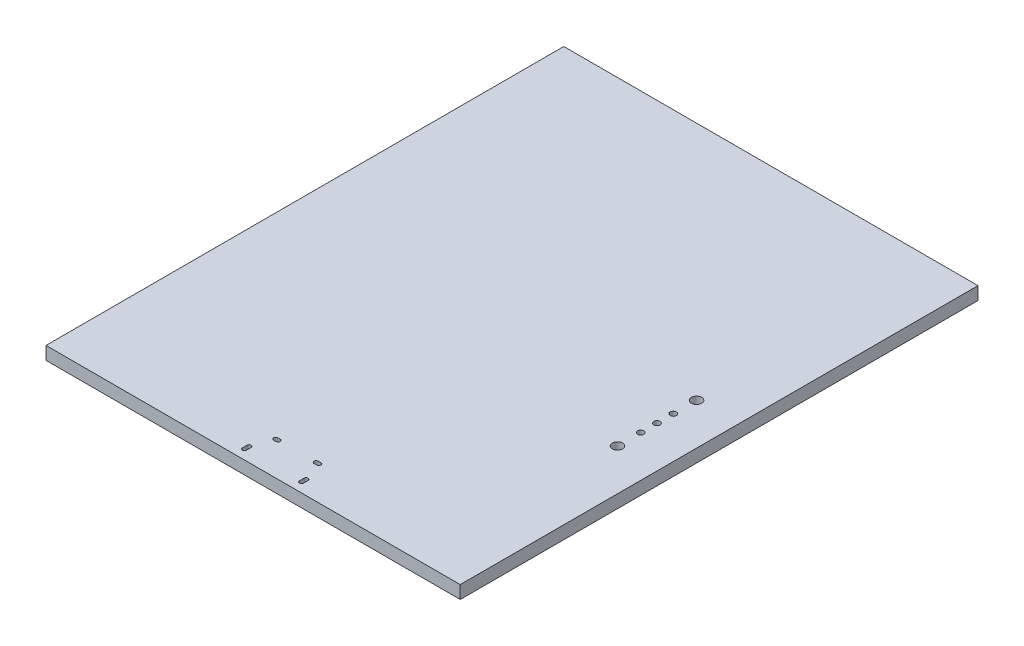
SolidWorks part; units mm, degrees
material "PCB Multi Layer"
ref_plane "Front Plane" through (0, 0, 0) normal (0, 0, 1) x (1, 0, 0)
ref_plane "Top Plane" through (0, 0, 0) normal (0, 1, 0) x (1, 0, 0)
ref_plane "Right Plane" through (0, 0, 0) normal (1, 0, 0) x (0, 0, -1)
sketch "Sketch1" plane through (0, 0, 0) normal (0, 1, 0) x (1, 0, 0)
  line L0 (-25.4, -31.75) -> (25.4, 31.75) construction
  line L1 (-25.4, 31.75) -> (25.4, 31.75)
  line L2 (-25.4, 31.75) -> (-25.4, -31.75)
  line L3 (-25.4, -31.75) -> (25.4, -31.75)
  line L4 (25.4, 31.75) -> (25.4, -31.75)
  dimension "D1" = 63.5
  dimension "D2" = 50.8
extrude "Boss-Extrude1" add sketch "Sketch1" along normal blind 1.5875
sketch "Sketch2" plane through (0, 1.5875, 0) normal (0, 1, 0) x (1, 0, 0)
  line L522 (-15.764, 14.9942) -> (-17.764, 14.9942)
  line L523 (-15.764, 15.9942) -> (-17.764, 15.9942)
  line L524 (-15.764, 15.9942) -> (-15.764, 14.9942)
  line L525 (-17.764, 15.9942) -> (-17.764, 14.9942)
  line L526 (-1.6002, 10.211) -> (-1.6002, 9.3474)
  line L527 (11.0676, -0.139) -> (11.5676, 0.361)
  line L528 (11.6969, -13.4784) -> (12.1969, -12.9784)
  line L529 (-15.764, 13.0892) -> (-17.764, 13.0892)
  line L530 (-15.764, 14.0892) -> (-17.764, 14.0892)
  line L531 (-15.764, 14.0892) -> (-15.764, 13.0892)
  line L532 (-17.764, 14.0892) -> (-17.764, 13.0892)
  line L533 (-8.51, 6.3982) -> (-10.54, 6.3982)
  line L534 (-8.51, 7.3182) -> (-10.54, 7.3182)
  line L535 (-8.51, 7.3182) -> (-8.51, 6.3982)
  line L536 (-10.54, 7.3182) -> (-10.54, 6.3982)
  line L537 (-9.779, 16.2562) -> (-9.779, 12.1922)
  line L538 (-8.001, 16.2562) -> (-8.001, 12.1922)
  line L539 (-9.779, 12.1922) -> (-8.001, 12.1922)
  line L540 (-9.779, 16.2562) -> (-8.001, 16.2562)
  line L541 (-9.263, 21.3522) -> (-9.263, 23.3522)
  line L542 (-8.263, 21.3522) -> (-8.263, 23.3522)
  line L543 (-8.263, 21.3522) -> (-9.263, 21.3522)
  line L544 (-8.263, 23.3522) -> (-9.263, 23.3522)
  line L545 (1.635, -15.1048) -> (-0.365, -15.1048)
  line L546 (1.635, -14.1048) -> (-0.365, -14.1048)
  line L547 (1.635, -14.1048) -> (1.635, -15.1048)
  line L548 (-0.365, -14.1048) -> (-0.365, -15.1048)
  line L549 (-0.46, -10.2858) -> (-0.46, -8.2558)
  line L550 (0.46, -10.2858) -> (0.46, -8.2558)
  line L551 (0.46, -10.2858) -> (-0.46, -10.2858)
  line L552 (0.46, -8.2558) -> (-0.46, -8.2558)
  line L553 (-0.365, -7.1198) -> (1.635, -7.1198)
  line L554 (-0.365, -8.1198) -> (1.635, -8.1198)
  line L555 (-0.365, -8.1198) -> (-0.365, -7.1198)
  line L556 (1.635, -8.1198) -> (1.635, -7.1198)
  line L557 (-0.373, 0.1432) -> (-0.373, 2.1432)
  line L561 (0.627, 0.1432) -> (0.627, 2.1432)
  line L562 (0.627, 0.1432) -> (-0.373, 0.1432)
  line L563 (0.627, 2.1432) -> (-0.373, 2.1432)
  line L564 (-1.643, 0.1432) -> (-1.643, 2.1432)
  line L565 (-0.643, 0.1432) -> (-0.643, 2.1432)
  line L566 (-0.643, 0.1432) -> (-1.643, 0.1432)
  line L567 (-0.643, 2.1432) -> (-1.643, 2.1432)
  line L571 (2.286, 21.1584) -> (-0.762, 21.1584)
  line L572 (-0.508, 21.1584) -> (-0.508, 20.2948)
  line L573 (0.1524, 20.2948) -> (0.1524, 21.1584)
  line L574 (-0.508, 20.2948) -> (0.1524, 20.2948)
  line L581 (1.3716, 21.1584) -> (1.3716, 20.2948)
  line L582 (1.3716, 20.2948) -> (2.032, 20.2948)
  line L583 (2.032, 20.2948) -> (2.032, 21.1584)
  line L584 (-0.762, 22.4284) -> (2.286, 22.4284)
  line L585 (1.0922, 23.292) -> (0.4318, 23.292)
  line L586 (0.4318, 23.292) -> (0.4318, 22.4284)
  line L587 (1.0922, 22.4284) -> (1.0922, 23.292)
  line L588 (2.286, 22.4284) -> (2.286, 21.1584)
  line L589 (-0.762, 21.1584) -> (-0.762, 22.4284)
  line L594 (6.555, -11.3248) -> (9.955, -11.3248)
  line L626 (6.555, -7.7248) -> (9.955, -7.7248)
  line L627 (9.955, -11.3248) -> (9.955, -7.7248)
  line L628 (6.555, -11.3248) -> (6.555, -7.7248)
  line L629 (8.001, 1.3972) -> (8.001, -2.6668)
  line L630 (9.779, 1.3972) -> (9.779, -2.6668)
  line L631 (8.001, -2.6668) -> (9.779, -2.6668)
  line L632 (8.001, 1.3972) -> (9.779, 1.3972)
  line L633 (7.24, 6.8102) -> (9.27, 6.8102)
  line L634 (7.24, 5.8902) -> (9.27, 5.8902)
  line L635 (7.24, 5.8902) -> (7.24, 6.8102)
  line L636 (9.27, 5.8902) -> (9.27, 6.8102)
  line L637 (15.74, -17.4148) -> (15.74, -19.4148)
  line L638 (14.74, -17.4148) -> (14.74, -19.4148)
  line L639 (14.74, -17.4148) -> (15.74, -17.4148)
  line L640 (14.74, -19.4148) -> (15.74, -19.4148)
  line L641 (14.351, 1.3972) -> (14.351, -2.6668)
  line L642 (16.129, 1.3972) -> (16.129, -2.6668)
  line L643 (14.351, -2.6668) -> (16.129, -2.6668)
  line L644 (14.351, 1.3972) -> (16.129, 1.3972)
  line L645 (15.105, 7.9852) -> (15.105, 5.9852)
  line L646 (14.105, 7.9852) -> (14.105, 5.9852)
  line L647 (14.105, 7.9852) -> (15.105, 7.9852)
  line L648 (14.105, 5.9852) -> (15.105, 5.9852)
  line L649 (13.835, 7.9852) -> (13.835, 5.9852)
  line L650 (12.835, 7.9852) -> (12.835, 5.9852)
  line L651 (12.835, 7.9852) -> (13.835, 7.9852)
  line L652 (12.835, 5.9852) -> (13.835, 5.9852)
  line L653 (-14.985, 10.1122) -> (-12.955, 10.1122)
  line L654 (-14.985, 9.1922) -> (-12.955, 9.1922)
  line L655 (-14.985, 9.1922) -> (-14.985, 10.1122)
  line L656 (-12.955, 9.1922) -> (-12.955, 10.1122)
  line L657 (-17.525, 10.1122) -> (-15.495, 10.1122)
  line L658 (-17.525, 9.1922) -> (-15.495, 9.1922)
  line L659 (-17.525, 9.1922) -> (-17.525, 10.1122)
  line L660 (-15.495, 9.1922) -> (-15.495, 10.1122)
  line L661 (-6.175, -19.4298) -> (-6.175, -17.3998)
  line L662 (-5.255, -19.4298) -> (-5.255, -17.3998)
  line L663 (-5.255, -19.4298) -> (-6.175, -19.4298)
  line L664 (-5.255, -17.3998) -> (-6.175, -17.3998)
  line L665 (-9.906, -18.4148) -> (-6.858, -18.4148)
  line L666 (-6.858, -20.1928) -> (-9.906, -20.1928)
  line L667 (-9.906, -20.1928) -> (-9.906, -18.4148)
  line L668 (-6.858, -18.4148) -> (-6.858, -20.1928)
  line L669 (-4.7, -4.6508) -> (-6.73, -4.6508)
  line L670 (-4.7, -3.7308) -> (-6.73, -3.7308)
  line L671 (-4.7, -3.7308) -> (-4.7, -4.6508)
  line L672 (-6.73, -3.7308) -> (-6.73, -4.6508)
  line L673 (-7.24, 17.9552) -> (-9.27, 17.9552)
  line L674 (-7.24, 18.8752) -> (-9.27, 18.8752)
  line L675 (-7.24, 18.8752) -> (-7.24, 17.9552)
  line L676 (-9.27, 18.8752) -> (-9.27, 17.9552)
  line L677 (-7.24, 16.6852) -> (-9.27, 16.6852)
  line L678 (-7.24, 17.6052) -> (-9.27, 17.6052)
  line L679 (-7.24, 17.6052) -> (-7.24, 16.6852)
  line L680 (-9.27, 17.6052) -> (-9.27, 16.6852)
  line L681 (-5.54, 3.4302) -> (-5.54, 5.4602)
  line L682 (-4.62, 3.4302) -> (-4.62, 5.4602)
  line L683 (-4.62, 3.4302) -> (-5.54, 3.4302)
  line L684 (-4.62, 5.4602) -> (-5.54, 5.4602)
  line L685 (-6.477, 9.2712) -> (-4.953, 9.2712)
  line L686 (-6.477, 13.5892) -> (-4.953, 13.5892)
  line L687 (-4.953, 13.5892) -> (-4.953, 9.2712)
  line L688 (-6.477, 13.5892) -> (-6.477, 9.2712)
  line L689 (-10.54, 8.5882) -> (-8.51, 8.5882)
  line L690 (-10.54, 7.6682) -> (-8.51, 7.6682)
  line L691 (-10.54, 7.6682) -> (-10.54, 8.5882)
  line L692 (-8.51, 7.6682) -> (-8.51, 8.5882)
  line L693 (-9.263, 23.8922) -> (-9.263, 25.8922)
  line L694 (-8.263, 23.8922) -> (-8.263, 25.8922)
  line L695 (-8.263, 23.8922) -> (-9.263, 23.8922)
  line L696 (-8.263, 25.8922) -> (-9.263, 25.8922)
  line L697 (1.659, -19.4148) -> (1.659, -17.4148)
  line L698 (2.659, -19.4148) -> (2.659, -17.4148)
  line L699 (2.659, -19.4148) -> (1.659, -19.4148)
  line L700 (2.659, -17.4148) -> (1.659, -17.4148)
  line L701 (0.635, -20.4468) -> (0.635, -16.3828)
  line L702 (-1.143, -20.4468) -> (-1.143, -16.3828)
  line L703 (0.635, -16.3828) -> (-1.143, -16.3828)
  line L704 (0.635, -20.4468) -> (-1.143, -20.4468)
  line L705 (-2.365, -19.4298) -> (-2.365, -17.3998)
  line L706 (-1.445, -19.4298) -> (-1.445, -17.3998)
  line L707 (-1.445, -19.4298) -> (-2.365, -19.4298)
  line L708 (-1.445, -17.3998) -> (-2.365, -17.3998)
  line L709 (1.635, -13.8348) -> (-0.365, -13.8348)
  line L710 (1.635, -12.8348) -> (-0.365, -12.8348)
  line L711 (1.635, -12.8348) -> (1.635, -13.8348)
  line L712 (-0.365, -12.8348) -> (-0.365, -13.8348)
  line L713 (1.65, -12.5248) -> (-0.38, -12.5248)
  line L714 (1.65, -11.6048) -> (-0.38, -11.6048)
  line L715 (1.65, -11.6048) -> (1.65, -12.5248)
  line L716 (-0.38, -11.6048) -> (-0.38, -12.5248)
  line L717 (-0.365, -5.8498) -> (1.635, -5.8498)
  line L718 (-0.365, -6.8498) -> (1.635, -6.8498)
  line L719 (-0.365, -6.8498) -> (-0.365, -5.8498)
  line L720 (1.635, -6.8498) -> (1.635, -5.8498)
  line L721 (-1.77, 23.7652) -> (-1.77, 25.7652)
  line L722 (-0.77, 23.7652) -> (-0.77, 25.7652)
  line L723 (-0.77, 23.7652) -> (-1.77, 23.7652)
  line L724 (-0.77, 25.7652) -> (-1.77, 25.7652)
  line L725 (2.04, 23.7652) -> (2.04, 25.7652)
  line L726 (3.04, 23.7652) -> (3.04, 25.7652)
  line L727 (3.04, 23.7652) -> (2.04, 23.7652)
  line L728 (3.04, 25.7652) -> (2.04, 25.7652)
  line L729 (0.254, 8.0774) -> (-2.794, 8.0774)
  line L730 (-2.54, 8.0774) -> (-2.54, 7.2138)
  line L731 (-1.8796, 7.2138) -> (-1.8796, 8.0774)
  line L732 (-2.54, 7.2138) -> (-1.8796, 7.2138)
  line L733 (-0.6604, 8.0774) -> (-0.6604, 7.2138)
  line L734 (-0.6604, 7.2138) -> (0, 7.2138)
  line L735 (0, 7.2138) -> (0, 8.0774)
  line L736 (-2.794, 9.3474) -> (0.254, 9.3474)
  line L737 (-0.9398, 10.211) -> (-1.6002, 10.211)
  line L738 (-0.9398, 9.3474) -> (-0.9398, 10.211)
  line L739 (0.254, 9.3474) -> (0.254, 8.0774)
  line L740 (-2.794, 8.0774) -> (-2.794, 9.3474)
  line L741 (11.049, -16.0018) -> (11.049, -11.9378)
  line L742 (9.271, -16.0018) -> (9.271, -11.9378)
  line L743 (11.049, -11.9378) -> (9.271, -11.9378)
  line L744 (11.049, -16.0018) -> (9.271, -16.0018)
  line L745 (10.287, -5.4608) -> (6.223, -5.4608)
  line L746 (10.287, -7.2388) -> (6.223, -7.2388)
  line L747 (6.223, -5.4608) -> (6.223, -7.2388)
  line L748 (10.287, -5.4608) -> (10.287, -7.2388)
  line L749 (8.644, -19.4148) -> (8.644, -17.4148)
  line L750 (9.644, -19.4148) -> (9.644, -17.4148)
  line L751 (9.644, -19.4148) -> (8.644, -19.4148)
  line L752 (9.644, -17.4148) -> (8.644, -17.4148)
  line L753 (7.374, -19.4148) -> (7.374, -17.4148)
  line L754 (8.374, -19.4148) -> (8.374, -17.4148)
  line L755 (8.374, -19.4148) -> (7.374, -19.4148)
  line L756 (8.374, -17.4148) -> (7.374, -17.4148)
  line L757 (5.588, -20.7008) -> (5.588, -17.3988)
  line L758 (7.112, -20.7008) -> (7.112, -17.3988)
  line L759 (7.112, -20.7008) -> (5.588, -20.7008)
  line L760 (7.112, -17.3988) -> (5.588, -17.3988)
  line L761 (5.255, 7.8752) -> (5.255, 9.9052)
  line L762 (6.175, 7.8752) -> (6.175, 9.9052)
  line L763 (6.175, 7.8752) -> (5.255, 7.8752)
  line L764 (6.175, 9.9052) -> (5.255, 9.9052)
  line L765 (6.553, 12.1792) -> (6.553, 7.3792)
  line L766 (9.653, 12.1792) -> (9.653, 7.3792)
  line L767 (9.653, 7.3792) -> (6.553, 7.3792)
  line L768 (9.653, 12.1792) -> (6.553, 12.1792)
  line L769 (5.85, 23.7652) -> (5.85, 25.7652)
  line L770 (6.85, 23.7652) -> (6.85, 25.7652)
  line L771 (6.85, 23.7652) -> (5.85, 23.7652)
  line L772 (6.85, 25.7652) -> (5.85, 25.7652)
  line L773 (9.555, 20.5152) -> (9.555, 16.3152)
  line L774 (6.955, 20.5152) -> (6.955, 16.3152)
  line L775 (6.955, 20.5152) -> (9.555, 20.5152)
  line L776 (6.955, 16.3152) -> (9.555, 16.3152)
  line L777 (11.168, 25.7652) -> (11.168, 23.7652)
  line L778 (10.168, 25.7652) -> (10.168, 23.7652)
  line L779 (10.168, 25.7652) -> (11.168, 25.7652)
  line L780 (10.168, 23.7652) -> (11.168, 23.7652)
  line L781 (9.858, 25.7802) -> (9.858, 23.7502)
  line L782 (8.938, 25.7802) -> (8.938, 23.7502)
  line L783 (8.938, 25.7802) -> (9.858, 25.7802)
  line L784 (8.938, 23.7502) -> (9.858, 23.7502)
  line L785 (8.588, 25.7802) -> (8.588, 23.7502)
  line L786 (7.668, 25.7802) -> (7.668, 23.7502)
  line L787 (7.668, 25.7802) -> (8.588, 25.7802)
  line L788 (7.668, 23.7502) -> (8.588, 23.7502)
  line L789 (14.43, -4.6998) -> (14.43, -6.7298)
  line L790 (13.51, -4.6998) -> (13.51, -6.7298)
  line L791 (13.51, -4.6998) -> (14.43, -4.6998)
  line L792 (13.51, -6.7298) -> (14.43, -6.7298)
  line L793 (12.573, -19.6848) -> (12.573, -16.3828)
  line L794 (14.097, -19.6848) -> (14.097, -16.3828)
  line L795 (14.097, -19.6848) -> (12.573, -19.6848)
  line L796 (14.097, -16.3828) -> (12.573, -16.3828)
  line L797 (14.351, -11.8108) -> (14.351, -15.8748)
  line L798 (16.129, -11.8108) -> (16.129, -15.8748)
  line L799 (14.351, -15.8748) -> (16.129, -15.8748)
  line L800 (14.351, -11.8108) -> (16.129, -11.8108)
  line L801 (13.51, 23.7502) -> (13.51, 25.7802)
  line L802 (14.43, 23.7502) -> (14.43, 25.7802)
  line L803 (14.43, 23.7502) -> (13.51, 23.7502)
  line L804 (14.43, 25.7802) -> (13.51, 25.7802)
  line L805 (15.74, 25.7652) -> (15.74, 23.7652)
  line L806 (14.74, 25.7652) -> (14.74, 23.7652)
  line L807 (14.74, 25.7652) -> (15.74, 25.7652)
  line L808 (14.74, 23.7652) -> (15.74, 23.7652)
  line L809 (16.05, 23.7502) -> (16.05, 25.7802)
  line L810 (16.97, 23.7502) -> (16.97, 25.7802)
  line L811 (16.97, 23.7502) -> (16.05, 23.7502)
  line L812 (16.97, 25.7802) -> (16.05, 25.7802)
  line L813 (17.32, 23.7502) -> (17.32, 25.7802)
  line L814 (18.24, 23.7502) -> (18.24, 25.7802)
  line L815 (18.24, 23.7502) -> (17.32, 23.7502)
  line L816 (18.24, 25.7802) -> (17.32, 25.7802)
  line L817 (13.089, 16.7802) -> (13.089, 18.7802)
  line L818 (14.089, 16.7802) -> (14.089, 18.7802)
  line L819 (14.089, 16.7802) -> (13.089, 16.7802)
  line L820 (14.089, 18.7802) -> (13.089, 18.7802)
  line L821 (16.05, 16.7652) -> (16.05, 18.7952)
  line L822 (16.97, 16.7652) -> (16.97, 18.7952)
  line L823 (16.97, 16.7652) -> (16.05, 16.7652)
  line L824 (16.97, 18.7952) -> (16.05, 18.7952)
  line L825 (15.74, 18.7802) -> (15.74, 16.7802)
  line L826 (14.74, 18.7802) -> (14.74, 16.7802)
  line L827 (14.74, 18.7802) -> (15.74, 18.7802)
  line L828 (14.74, 16.7802) -> (15.74, 16.7802)
  line L829 (-0.373, -2.3968) -> (-0.373, -0.3968)
  line L830 (0.627, -2.3968) -> (0.627, -0.3968)
  line L831 (0.627, -2.3968) -> (-0.373, -2.3968)
  line L832 (0.627, -0.3968) -> (-0.373, -0.3968)
  line L833 (-0.643, -0.3968) -> (-0.643, -2.3968)
  line L834 (-1.643, -0.3968) -> (-1.643, -2.3968)
  line L835 (-1.643, -0.3968) -> (-0.643, -0.3968)
  line L836 (-1.643, -2.3968) -> (-0.643, -2.3968)
  line L837 (10.168, 21.2252) -> (10.168, 23.2252)
  line L838 (11.168, 21.2252) -> (11.168, 23.2252)
  line L839 (11.168, 21.2252) -> (10.168, 21.2252)
  line L840 (11.168, 23.2252) -> (10.168, 23.2252)
  line L841 (-17.478, -18.7948) -> (-17.478, -16.7648)
  line L842 (-16.558, -18.7948) -> (-16.558, -16.7648)
  line L843 (-16.558, -18.7948) -> (-17.478, -18.7948)
  line L844 (-16.558, -16.7648) -> (-17.478, -16.7648)
  line L845 (-15.926, -15.3798) -> (-15.926, -20.1798)
  line L846 (-12.826, -15.3798) -> (-12.826, -20.1798)
  line L847 (-12.826, -20.1798) -> (-15.926, -20.1798)
  line L848 (-12.826, -15.3798) -> (-15.926, -15.3798)
  line L849 (-9.145, -17.0968) -> (-11.175, -17.0968)
  line L850 (-9.145, -16.1768) -> (-11.175, -16.1768)
  line L851 (-9.145, -16.1768) -> (-9.145, -17.0968)
  line L852 (-11.175, -16.1768) -> (-11.175, -17.0968)
  line L853 (-12.573, -8.6358) -> (-16.637, -8.6358)
  line L854 (-12.573, -10.4138) -> (-16.637, -10.4138)
  line L855 (-16.637, -8.6358) -> (-16.637, -10.4138)
  line L856 (-12.573, -8.6358) -> (-12.573, -10.4138)
  line L857 (-15.62, -7.1598) -> (-13.59, -7.1598)
  line L858 (-15.62, -8.0798) -> (-13.59, -8.0798)
  line L859 (-15.62, -8.0798) -> (-15.62, -7.1598)
  line L860 (-13.59, -8.0798) -> (-13.59, -7.1598)
  line L861 (-17.137, -4.1748) -> (-17.137, -2.1748)
  line L862 (-16.137, -4.1748) -> (-16.137, -2.1748)
  line L863 (-16.137, -4.1748) -> (-17.137, -4.1748)
  line L864 (-16.137, -2.1748) -> (-17.137, -2.1748)
  line L865 (-16.137, 0.3652) -> (-16.137, -1.6348)
  line L866 (-17.137, 0.3652) -> (-17.137, -1.6348)
  line L867 (-17.137, 0.3652) -> (-16.137, 0.3652)
  line L868 (-17.137, -1.6348) -> (-16.137, -1.6348)
  line L869 (-10.16, 12.1922) -> (-10.16, 16.2562)
  line L870 (-11.938, 12.1922) -> (-11.938, 16.2562)
  line L871 (-10.16, 16.2562) -> (-11.938, 16.2562)
  line L872 (-10.16, 12.1922) -> (-11.938, 12.1922)
  line L873 (7.747, -20.9548) -> (3.683, -20.9548)
  line L874 (7.747, -22.7328) -> (3.683, -22.7328)
  line L875 (3.683, -20.9548) -> (3.683, -22.7328)
  line L876 (7.747, -20.9548) -> (7.747, -22.7328)
  line L877 (2.929, -17.0018) -> (2.929, -15.0018)
  line L878 (3.929, -17.0018) -> (3.929, -15.0018)
  line L879 (3.929, -17.0018) -> (2.929, -17.0018)
  line L880 (3.929, -15.0018) -> (2.929, -15.0018)
  line L881 (1.65, -16.3348) -> (-0.38, -16.3348)
  line L882 (1.65, -15.4148) -> (-0.38, -15.4148)
  line L883 (1.65, -15.4148) -> (1.65, -16.3348)
  line L884 (-0.38, -15.4148) -> (-0.38, -16.3348)
  line L885 (4.445, -12.0648) -> (4.445, -8.0008)
  line L886 (2.667, -12.0648) -> (2.667, -8.0008)
  line L887 (4.445, -8.0008) -> (2.667, -8.0008)
  line L888 (4.445, -12.0648) -> (2.667, -12.0648)
  line L889 (10.7, -8.4248) -> (11.2, -7.9248)
  line L890 (10.7, -7.9248) -> (10.7, -11.1248)
  line L891 (14.7, -7.9248) -> (14.7, -11.1248)
  line L892 (10.7, -11.1248) -> (14.7, -11.1248)
  line L893 (10.7, -7.9248) -> (14.7, -7.9248)
  line L894 (2.167, 0.1432) -> (2.167, 2.1432)
  line L895 (3.167, 0.1432) -> (3.167, 2.1432)
  line L896 (3.167, 0.1432) -> (2.167, 0.1432)
  line L897 (3.167, 2.1432) -> (2.167, 2.1432)
  line L898 (0.897, 0.1432) -> (0.897, 2.1432)
  line L899 (1.897, 0.1432) -> (1.897, 2.1432)
  line L900 (1.897, 0.1432) -> (0.897, 0.1432)
  line L901 (1.897, 2.1432) -> (0.897, 2.1432)
  line L902 (11.065, 0.3652) -> (11.065, -1.6348)
  line L903 (13.065, 0.3652) -> (13.065, -1.6348)
  line L904 (11.065, -1.6348) -> (13.065, -1.6348)
  line L905 (11.065, 0.3652) -> (13.065, 0.3652)
  line L906 (-2.913, 0.1432) -> (-2.913, 2.1432)
  line L907 (-1.913, 0.1432) -> (-1.913, 2.1432)
  line L908 (-1.913, 0.1432) -> (-2.913, 0.1432)
  line L909 (-1.913, 2.1432) -> (-2.913, 2.1432)
  line L910 (3.477, 0.1282) -> (3.477, 2.1582)
  line L911 (4.397, 0.1282) -> (4.397, 2.1582)
  line L912 (4.397, 0.1282) -> (3.477, 0.1282)
  line L913 (4.397, 2.1582) -> (3.477, 2.1582)
  line L914 (12.445, 7.6682) -> (10.415, 7.6682)
  line L915 (12.445, 8.5882) -> (10.415, 8.5882)
  line L916 (12.445, 8.5882) -> (12.445, 7.6682)
  line L917 (10.415, 8.5882) -> (10.415, 7.6682)
  line L918 (-5.445, 8.1202) -> (-3.445, 8.1202)
  line L919 (-5.445, 7.1202) -> (-3.445, 7.1202)
  line L920 (-5.445, 7.1202) -> (-5.445, 8.1202)
  line L921 (-3.445, 7.1202) -> (-3.445, 8.1202)
  line L922 (12.445, 6.5252) -> (10.415, 6.5252)
  line L923 (12.445, 7.4452) -> (10.415, 7.4452)
  line L924 (12.445, 7.4452) -> (12.445, 6.5252)
  line L925 (10.415, 7.4452) -> (10.415, 6.5252)
  line L926 (4.362, 6.0182) -> (4.762, 6.0182)
  line L927 (-2.838, 6.0182) -> (-3.238, 6.0182)
  line L928 (-2.838, 3.4182) -> (4.362, 3.4182)
  line L929 (-3.202, 3.1182) -> (4.762, 3.1182)
  line L930 (-3.238, 6.4182) -> (4.762, 6.4182)
  line L931 (4.762, 3.1182) -> (4.762, 6.4182)
  line L932 (4.362, 6.0182) -> (4.362, 3.4182)
  line L933 (-3.238, 3.1182) -> (-3.238, 6.4182)
  line L934 (-2.838, 3.4182) -> (-2.838, 6.0182)
  line L935 (-1.23, 3.8102) -> (-1.23, 4.8262)
  line L936 (-1.23, 4.8262) -> (-2.246, 4.8262)
  line L937 (-2.246, 4.8262) -> (-2.246, 3.8102)
  line L938 (-2.246, 3.8102) -> (-1.23, 3.8102)
  line L939 (4.318, 15.4942) -> (4.318, 11.4302)
  line L940 (6.096, 15.4942) -> (6.096, 11.4302)
  line L941 (4.318, 11.4302) -> (6.096, 11.4302)
  line L942 (4.318, 15.4942) -> (6.096, 15.4942)
  line L943 (18.24, 15.6202) -> (18.24, 13.5902)
  line L944 (17.32, 15.6202) -> (17.32, 13.5902)
  line L945 (17.32, 15.6202) -> (18.24, 15.6202)
  line L946 (17.32, 13.5902) -> (18.24, 13.5902)
  line L947 (-1.524, 21.1584) -> (-4.572, 21.1584)
  line L948 (-4.318, 21.1584) -> (-4.318, 20.2948)
  line L949 (-3.6576, 20.2948) -> (-3.6576, 21.1584)
  line L950 (-4.318, 20.2948) -> (-3.6576, 20.2948)
  line L951 (-2.4384, 21.1584) -> (-2.4384, 20.2948)
  line L952 (-2.4384, 20.2948) -> (-1.778, 20.2948)
  line L953 (-1.778, 20.2948) -> (-1.778, 21.1584)
  line L954 (-4.572, 22.4284) -> (-1.524, 22.4284)
  line L955 (-2.7178, 23.292) -> (-3.3782, 23.292)
  line L956 (-3.3782, 23.292) -> (-3.3782, 22.4284)
  line L957 (-2.7178, 22.4284) -> (-2.7178, 23.292)
  line L958 (-1.524, 22.4284) -> (-1.524, 21.1584)
  line L959 (-4.572, 21.1584) -> (-4.572, 22.4284)
  line L960 (6.096, 21.1584) -> (3.048, 21.1584)
  line L961 (3.302, 21.1584) -> (3.302, 20.2948)
  line L962 (3.9624, 20.2948) -> (3.9624, 21.1584)
  line L963 (3.302, 20.2948) -> (3.9624, 20.2948)
  line L964 (5.1816, 21.1584) -> (5.1816, 20.2948)
  line L965 (5.1816, 20.2948) -> (5.842, 20.2948)
  line L966 (5.842, 20.2948) -> (5.842, 21.1584)
  line L967 (3.048, 22.4284) -> (6.096, 22.4284)
  line L968 (4.9022, 23.292) -> (4.2418, 23.292)
  line L969 (4.2418, 23.292) -> (4.2418, 22.4284)
  line L970 (4.9022, 22.4284) -> (4.9022, 23.292)
  line L971 (6.096, 22.4284) -> (6.096, 21.1584)
  line L972 (3.048, 21.1584) -> (3.048, 22.4284)
  line L973 (18.24, 23.2402) -> (18.24, 21.2102)
  line L974 (17.32, 23.2402) -> (17.32, 21.2102)
  line L975 (17.32, 23.2402) -> (18.24, 23.2402)
  line L976 (17.32, 21.2102) -> (18.24, 21.2102)
  line L977 (13.51, 21.2102) -> (13.51, 23.2402)
  line L978 (14.43, 21.2102) -> (14.43, 23.2402)
  line L979 (14.43, 21.2102) -> (13.51, 21.2102)
  line L980 (14.43, 23.2402) -> (13.51, 23.2402)
  line L981 (16.97, 23.2402) -> (16.97, 21.2102)
  line L982 (16.05, 23.2402) -> (16.05, 21.2102)
  line L983 (16.05, 23.2402) -> (16.97, 23.2402)
  line L984 (16.05, 21.2102) -> (16.97, 21.2102)
  line L985 (15.74, 23.2252) -> (15.74, 21.2252)
  line L986 (14.74, 23.2252) -> (14.74, 21.2252)
  line L987 (14.74, 23.2252) -> (15.74, 23.2252)
  line L988 (14.74, 21.2252) -> (15.74, 21.2252)
  line L989 (-12.573, -11.1758) -> (-16.637, -11.1758)
  line L990 (-12.573, -12.9538) -> (-16.637, -12.9538)
  line L991 (-16.637, -11.1758) -> (-16.637, -12.9538)
  line L992 (-12.573, -11.1758) -> (-12.573, -12.9538)
  line L993 (-15.62, -20.4948) -> (-13.59, -20.4948)
  line L994 (-15.62, -21.4148) -> (-13.59, -21.4148)
  line L995 (-15.62, -21.4148) -> (-15.62, -20.4948)
  line L996 (-13.59, -21.4148) -> (-13.59, -20.4948)
  line L997 (-19.105, 17.4752) -> (-19.105, 26.9752)
  line L998 (-10.105, 17.4752) -> (-10.105, 26.9752)
  line L999 (-19.105, 17.4752) -> (-10.105, 17.4752)
  line L1000 (-19.105, 26.9752) -> (-10.105, 26.9752)
  line L1001 (-12.02, 8.2652) -> (-11.42, 7.6652)
  line L1002 (-11.42, 8.2652) -> (-16.52, 8.2652)
  line L1003 (-11.42, 3.1652) -> (-16.52, 3.1652)
  line L1004 (-16.52, 8.2652) -> (-16.52, 3.1652)
  line L1005 (-11.42, 8.2652) -> (-11.42, 3.1652)
  line L1006 (11.7, -12.9698) -> (11.7, -14.9698)
  line L1007 (13.7, -12.9698) -> (13.7, -14.9698)
  line L1008 (11.7, -14.9698) -> (13.7, -14.9698)
  line L1009 (11.7, -12.9698) -> (13.7, -12.9698)
  line L1010 (-3.945, -17.4148) -> (-3.945, -19.4148)
  line L1011 (-4.945, -17.4148) -> (-4.945, -19.4148)
  line L1012 (-4.945, -17.4148) -> (-3.945, -17.4148)
  line L1013 (-4.945, -19.4148) -> (-3.945, -19.4148)
  line L1014 (-2.675, -17.4148) -> (-2.675, -19.4148)
  line L1015 (-3.675, -17.4148) -> (-3.675, -19.4148)
  line L1016 (-3.675, -17.4148) -> (-2.675, -17.4148)
  line L1017 (-3.675, -19.4148) -> (-2.675, -19.4148)
  line L1018 (11.184, -19.4148) -> (11.184, -17.4148)
  line L1019 (12.184, -19.4148) -> (12.184, -17.4148)
  line L1020 (12.184, -19.4148) -> (11.184, -19.4148)
  line L1021 (12.184, -17.4148) -> (11.184, -17.4148)
  line L1022 (4.961, -9.7628) -> (4.961, -7.7628)
  line L1023 (5.961, -9.7628) -> (5.961, -7.7628)
  line L1024 (5.961, -9.7628) -> (4.961, -9.7628)
  line L1025 (5.961, -7.7628) -> (4.961, -7.7628)
  line L1026 (8.45, -16.1048) -> (7.85, -16.7048)
  line L1027 (8.45, -16.7048) -> (8.45, -12.5048)
  line L1028 (4.25, -16.7048) -> (4.25, -12.5048)
  line L1029 (8.45, -12.5048) -> (4.25, -12.5048)
  line L1030 (8.45, -16.7048) -> (4.25, -16.7048)
  line L1031 (3.056, -19.4148) -> (3.056, -17.4148)
  line L1032 (4.056, -19.4148) -> (4.056, -17.4148)
  line L1033 (4.056, -19.4148) -> (3.056, -19.4148)
  line L1034 (4.056, -17.4148) -> (3.056, -17.4148)
  line L1035 (9.914, -19.4148) -> (9.914, -17.4148)
  line L1036 (10.914, -19.4148) -> (10.914, -17.4148)
  line L1037 (10.914, -19.4148) -> (9.914, -19.4148)
  line L1038 (10.914, -17.4148) -> (9.914, -17.4148)
  line L1039 (13.7, -12.5648) -> (11.7, -12.5648)
  line L1040 (13.7, -11.5648) -> (11.7, -11.5648)
  line L1041 (13.7, -11.5648) -> (13.7, -12.5648)
  line L1042 (11.7, -11.5648) -> (11.7, -12.5648)
  line L1043 (11.89, -4.6998) -> (11.89, -6.7298)
  line L1044 (10.97, -4.6998) -> (10.97, -6.7298)
  line L1045 (10.97, -4.6998) -> (11.89, -4.6998)
  line L1046 (10.97, -6.7298) -> (11.89, -6.7298)
  line L1047 (16.389, 9.8652) -> (15.789, 9.2652)
  line L1048 (16.389, 9.2652) -> (16.389, 14.8652)
  line L1049 (10.789, 9.2652) -> (10.789, 14.8652)
  line L1050 (16.389, 14.8652) -> (10.789, 14.8652)
  line L1051 (16.389, 9.2652) -> (10.789, 9.2652)
  line L1052 (1.016, 10.6682) -> (-3.556, 10.6682)
  line L1053 (-3.556, 13.4622) -> (1.016, 13.4622)
  line L1054 (1.016, 10.6682) -> (1.016, 13.4622)
  line L1055 (-3.556, 10.6682) -> (-3.556, 13.4622)
  line L1056 (17.645, 4.1752) -> (17.645, 2.1752)
  line L1057 (16.645, 4.1752) -> (16.645, 2.1752)
  line L1058 (16.645, 4.1752) -> (17.645, 4.1752)
  line L1059 (16.645, 2.1752) -> (17.645, 2.1752)
  line L1060 (6.096, 15.6212) -> (6.096, 19.6852)
  line L1061 (4.318, 15.6212) -> (4.318, 19.6852)
  line L1062 (6.096, 19.6852) -> (4.318, 19.6852)
  line L1063 (6.096, 15.6212) -> (4.318, 15.6212)
  line L1064 (17.399, 10.0332) -> (17.399, 13.3352)
  line L1065 (18.923, 10.0332) -> (18.923, 13.3352)
  line L1066 (18.923, 10.0332) -> (17.399, 10.0332)
  line L1067 (18.923, 13.3352) -> (17.399, 13.3352)
  line L1068 (3.762, 18.1602) -> (3.762, 16.1302)
  line L1069 (2.842, 18.1602) -> (2.842, 16.1302)
  line L1070 (2.842, 18.1602) -> (3.762, 18.1602)
  line L1071 (2.842, 16.1302) -> (3.762, 16.1302)
  line L1072 (-4.953, 18.6692) -> (-6.477, 18.6692)
  line L1073 (-4.953, 14.3512) -> (-6.477, 14.3512)
  line L1074 (-6.477, 14.3512) -> (-6.477, 18.6692)
  line L1075 (-4.953, 14.3512) -> (-4.953, 18.6692)
  line L1076 (-2.97, 15.7102) -> (-2.97, 14.5102)
  line L1077 (-3.57, 15.1102) -> (-2.37, 15.1102)
  line L1078 (1.43, 17.8102) -> (0.33, 18.9102)
  line L1079 (-3.97, 18.9102) -> (-3.97, 14.1102)
  line L1080 (1.43, 17.8102) -> (1.43, 14.1102)
  line L1081 (-3.97, 14.1102) -> (1.43, 14.1102)
  line L1082 (-3.97, 18.9102) -> (0.33, 18.9102)
  line L1083 (2.922, 11.0012) -> (4.952, 11.0012)
  line L1084 (2.922, 10.0812) -> (4.952, 10.0812)
  line L1085 (2.922, 10.0812) -> (2.922, 11.0012)
  line L1086 (4.952, 10.0812) -> (4.952, 11.0012)
  line L1087 (4.318, 11.4302) -> (4.318, 15.4942)
  line L1088 (2.54, 11.4302) -> (2.54, 15.4942)
  line L1089 (4.318, 15.4942) -> (2.54, 15.4942)
  line L1090 (4.318, 11.4302) -> (2.54, 11.4302)
  line L1091 (12.603, 20.5152) -> (12.603, 16.3152)
  line L1092 (10.003, 20.5152) -> (10.003, 16.3152)
  line L1093 (10.003, 20.5152) -> (12.603, 20.5152)
  line L1094 (10.003, 16.3152) -> (12.603, 16.3152)
  line L1095 (13.415, 3.6402) -> (10.715, 3.6402)
  line L1096 (13.415, 1.4402) -> (10.715, 1.4402)
  line L1097 (10.715, 3.6402) -> (10.715, 1.4402)
  line L1098 (13.415, 3.6402) -> (13.415, 1.4402)
  line L1099 (18.923, 19.1772) -> (18.923, 15.8752)
  line L1100 (17.399, 19.1772) -> (17.399, 15.8752)
  line L1101 (17.399, 19.1772) -> (18.923, 19.1772)
  line L1102 (17.399, 15.8752) -> (18.923, 15.8752)
  line L1103 (11.478, 23.7502) -> (11.478, 25.7802)
  line L1104 (12.398, 23.7502) -> (12.398, 25.7802)
  line L1105 (12.398, 23.7502) -> (11.478, 23.7502)
  line L1106 (12.398, 25.7802) -> (11.478, 25.7802)
  line L1107 (-12.651, -6.1398) -> (-12.651, -6.5398)
  line L1108 (-12.651, 1.0602) -> (-12.651, 1.4602)
  line L1109 (-15.251, 1.0602) -> (-15.251, -6.1398)
  line L1110 (-15.551, 1.4242) -> (-15.551, -6.5398)
  line L1111 (-12.251, 1.4602) -> (-12.251, -6.5398)
  line L1112 (-15.551, -6.5398) -> (-12.251, -6.5398)
  line L1113 (-12.651, -6.1398) -> (-15.251, -6.1398)
  line L1114 (-15.551, 1.4602) -> (-12.251, 1.4602)
  line L1115 (-15.251, 1.0602) -> (-12.651, 1.0602)
  line L1116 (-14.859, -0.5478) -> (-13.843, -0.5478)
  line L1117 (-13.843, -0.5478) -> (-13.843, 0.4682)
  line L1118 (-13.843, 0.4682) -> (-14.859, 0.4682)
  line L1119 (-14.859, 0.4682) -> (-14.859, -0.5478)
  line L1120 (-19.685, 6.2232) -> (-17.145, 6.2232)
  line L1121 (-19.685, 1.1432) -> (-19.685, 8.7632)
  line L1122 (-17.145, 1.1432) -> (-19.685, 1.1432)
  line L1123 (-17.145, 8.7632) -> (-17.145, 1.1432)
  line L1124 (-19.685, 8.7632) -> (-17.145, 8.7632)
  line L1125 (-2.98, -32.952) -> (-2.78, -33.152)
  line L1126 (-2.03, -32.402) -> (-2.03, -32.952)
  line L1127 (-2.33, -32.402) -> (-2.03, -32.402)
  line L1128 (5.52, -32.952) -> (5.32, -33.152)
  line L1129 (4.57, -32.402) -> (4.57, -32.952)
  line L1130 (4.87, -32.402) -> (4.57, -32.402)
  line L1131 (-2.58, -26.952) -> (-2.58, -32.402)
  line L1132 (5.12, -26.952) -> (5.12, -32.452)
  line L1133 (-2.03, -32.952) -> (4.57, -32.952)
  line L1134 (-2.58, -26.952) -> (5.12, -26.952)
  line L1135 (12.398, 23.2402) -> (12.398, 21.2102)
  line L1136 (11.478, 23.2402) -> (11.478, 21.2102)
  line L1137 (11.478, 23.2402) -> (12.398, 23.2402)
  line L1138 (11.478, 21.2102) -> (12.398, 21.2102)
  line L1139 (9.858, 23.2402) -> (9.858, 21.2102)
  line L1140 (8.938, 23.2402) -> (8.938, 21.2102)
  line L1141 (8.938, 23.2402) -> (9.858, 23.2402)
  line L1142 (8.938, 21.2102) -> (9.858, 21.2102)
  line L1143 (-1.913, -0.3968) -> (-1.913, -2.3968)
  line L1144 (-2.913, -0.3968) -> (-2.913, -2.3968)
  line L1145 (-2.913, -0.3968) -> (-1.913, -0.3968)
  line L1146 (-2.913, -2.3968) -> (-1.913, -2.3968)
  line L1147 (8.588, 23.2402) -> (8.588, 21.2102)
  line L1148 (7.668, 23.2402) -> (7.668, 21.2102)
  line L1149 (7.668, 23.2402) -> (8.588, 23.2402)
  line L1150 (7.668, 21.2102) -> (8.588, 21.2102)
  line L1151 (-10.493, 3.6842) -> (-10.493, 5.7142)
  line L1152 (-9.573, 3.6842) -> (-9.573, 5.7142)
  line L1153 (-9.573, 3.6842) -> (-10.493, 3.6842)
  line L1154 (-9.573, 5.7142) -> (-10.493, 5.7142)
  line L1155 (-2.35, -5.7948) -> (-1.35, -6.7948)
  line L1156 (-2.35, -5.7948) -> (-11.35, -5.7948)
  line L1157 (-1.35, -15.7948) -> (-11.35, -15.7948)
  line L1158 (-11.35, -5.7948) -> (-11.35, -15.7948)
  line L1159 (-1.35, -6.7948) -> (-1.35, -15.7948)
  line L1160 (-7.493, 24.3842) -> (-4.953, 24.3842)
  line L1161 (-7.493, 19.3042) -> (-7.493, 26.9242)
  line L1162 (-4.953, 19.3042) -> (-7.493, 19.3042)
  line L1163 (-4.953, 26.9242) -> (-4.953, 19.3042)
  line L1164 (-7.493, 26.9242) -> (-4.953, 26.9242)
  line L1165 (16.51, -12.6998) -> (19.05, -12.6998)
  line L1166 (16.51, -17.7798) -> (16.51, -10.1598)
  line L1167 (19.05, -17.7798) -> (16.51, -17.7798)
  line L1168 (19.05, -10.1598) -> (19.05, -17.7798)
  line L1169 (16.51, -10.1598) -> (19.05, -10.1598)
  line L1170 (18.32, -7.5898) -> (22.32, -7.5898)
  line L1171 (26.72, -1.5398) -> (27.32, -1.7398)
  line L1172 (26.72, -1.5398) -> (27.32, -1.3398)
  line L1173 (26.72, -1.1398) -> (27.32, -1.3398)
  line L1174 (26.72, -1.1398) -> (27.32, -0.9398)
  line L1175 (26.72, -0.7398) -> (27.32, -0.9398)
  line L1176 (26.72, -0.7398) -> (27.32, -0.5398)
  line L1177 (26.72, -1.9398) -> (27.32, -2.1398)
  line L1178 (26.72, -1.9398) -> (27.32, -1.7398)
  line L1179 (26.72, -2.3398) -> (27.32, -2.1398)
  line L1180 (18.32, 2.4102) -> (22.32, 2.4102)
  line L1181 (27.32, -0.5398) -> (22.32, -0.5398)
  line L1182 (27.32, -2.5398) -> (27.32, -0.5398)
  line L1183 (26.72, -2.3398) -> (27.32, -2.5398)
  line L1184 (22.32, -2.5398) -> (27.32, -2.5398)
  line L1185 (22.32, -7.5898) -> (22.32, 2.4102)
  line L1186 (18.32, -7.5898) -> (18.32, 2.4102)
  line L1187 (-25.4, 31.7502) -> (-25.4, -31.7498)
  line L1188 (25.4, -31.7498) -> (25.4, 31.7502)
  line L1189 (25.4, -31.7498) -> (-25.4, -31.7498)
  line L1190 (25.4, 31.7502) -> (-25.4, 31.7502)
  circle A0 centre (-24.13, -30.4798) radius 0.508
  circle A1 centre (-1.7311, 4.3182) radius 0.254
  circle A2 centre (-18.415, 7.614) radius 0.4255
  circle A3 centre (-6.223, 25.6645) radius 0.4255
  circle A4 centre (-14.351, -0.0311) radius 0.254
  circle A5 centre (17.78, -11.4347) radius 0.4255
  circle A6 centre (24.13, -30.4798) radius 0.508
  circle A7 centre (20.955, 27.3052) radius 0.508
  circle A8 centre (-6.6116, -17.7112) radius 0.127
  circle A9 centre (5.8954, 11.7782) radius 0.127
  circle A10 centre (-16.5836, -15.7808) radius 0.127
  circle A11 centre (-19.685, 15.8752) radius 0.508
  circle A12 centre (9.9553, -7.9396) radius 0.15
  circle A13 centre (2.012, 4.3182) radius 0.254
  circle A14 centre (3.262, 4.3182) radius 0.254
  circle A15 centre (-0.488, 4.3182) radius 0.254
  circle A16 centre (0.762, 4.3182) radius 0.254
  circle A17 centre (-19.4997, 16.7604) radius 0.101
  circle A18 centre (-12.0849, 8.9599) radius 0.15
  circle A19 centre (9.1947, -16.59) radius 0.15
  circle A20 centre (17.3837, 9.88) radius 0.101
  circle A21 centre (-3.9878, 10.719) radius 0.127
  circle A22 centre (-14.351, -3.7898) radius 0.254
  circle A23 centre (-14.351, -5.0398) radius 0.254
  circle A24 centre (-14.351, -1.2898) radius 0.254
  circle A25 centre (-14.351, -2.5398) radius 0.254
  circle A26 centre (-18.415, 4.9532) radius 0.4255
  circle A27 centre (-18.415, 2.4132) radius 0.4255
  arc A28 (-2.9795, -32.9518) -> (-2.5801, -32.4523) centre (-3.1946, -32.3703) ccw
  arc A29 (-2.7795, -33.1517) -> (-2.33, -32.4022) centre (-3.1579, -32.4152) ccw
  arc A30 (5.12, -32.4523) -> (5.5195, -32.9518) centre (5.7346, -32.3703) ccw
  arc A31 (4.87, -32.4022) -> (5.3194, -33.1517) centre (5.6979, -32.4152) ccw
  circle A32 centre (-1.38, -27.602) radius 0.25
  circle A33 centre (-1.38, -27.602) radius 0.25
  circle A34 centre (-1.08, -27.602) radius 0.25
  circle A35 centre (-1.08, -27.602) radius 0.25
  circle A36 centre (3.62, -27.602) radius 0.25
  circle A37 centre (3.62, -27.602) radius 0.25
  circle A38 centre (3.92, -27.602) radius 0.25
  circle A39 centre (3.92, -27.602) radius 0.25
  circle A40 centre (-2.23, -30.027) radius 0.25
  circle A41 centre (-2.23, -30.027) radius 0.25
  circle A42 centre (-2.23, -30.577) radius 0.25
  circle A43 centre (-2.23, -30.577) radius 0.25
  circle A44 centre (4.77, -30.577) radius 0.25
  circle A45 centre (4.77, -30.577) radius 0.25
  circle A46 centre (4.77, -30.027) radius 0.25
  circle A47 centre (4.77, -30.027) radius 0.25
  circle A48 centre (-1.4649, -6.0501) radius 0.101
  circle A49 centre (-6.223, 23.1142) radius 0.4254
  circle A50 centre (-6.223, 20.5742) radius 0.4255
  circle A51 centre (17.78, -13.9698) radius 0.4255
  circle A52 centre (17.78, -16.5098) radius 0.4254
  circle A53 centre (20.32, -4.5398) radius 0.3817
  circle A54 centre (20.32, -7.3898) radius 0.6318
  circle A55 centre (20.32, -0.5398) radius 0.3817
  circle A56 centre (20.32, 2.3102) radius 0.6318
  circle A57 centre (20.32, -2.5398) radius 0.3817
sketch "Sketch3" plane through (0, 1.5875, 0) normal (0, 1, 0) x (1, 0, 0)
  line L0 (-1.38, -27.352) -> (-1.08, -27.352)
  line L1 (-1.38, -27.852) -> (-1.08, -27.852)
  line L2 (3.57, -27.352) -> (3.92, -27.352)
  line L3 (3.57, -27.852) -> (3.92, -27.852)
  line L4 (4.52, -30.027) -> (4.52, -30.577)
  line L5 (5.02, -30.027) -> (5.02, -30.577)
  line L6 (-1.98, -30.027) -> (-1.98, -30.577)
  line L7 (-2.48, -30.027) -> (-2.48, -30.577)
  circle A5 centre (20.32, -7.3898) radius 0.6318 construction
  circle A6 centre (20.32, -4.5398) radius 0.3817 construction
  circle A7 centre (20.32, -2.5398) radius 0.3817 construction
  circle A8 centre (20.32, -0.5398) radius 0.3817 construction
  circle A9 centre (20.32, 2.3102) radius 0.6318 construction
  circle A10 centre (20.32, -7.3898) radius 0.6318
  circle A12 centre (20.32, -4.5398) radius 0.3817
  arc A18 (-1.08, -27.852) -> (-1.08, -27.352) centre (-1.08, -27.602) ccw
  arc A19 (-1.38, -27.352) -> (-1.38, -27.852) centre (-1.38, -27.602) ccw
  arc A20 (3.57, -27.352) -> (3.57, -27.852) centre (3.57, -27.602) ccw
  arc A21 (3.92, -27.852) -> (3.92, -27.352) centre (3.92, -27.602) ccw
  arc A22 (5.02, -30.027) -> (4.52, -30.027) centre (4.77, -30.027) ccw
  arc A23 (4.52, -30.577) -> (5.02, -30.577) centre (4.77, -30.577) ccw
  arc A24 (-2.48, -30.577) -> (-1.98, -30.577) centre (-2.23, -30.577) ccw
  arc A25 (-1.98, -30.027) -> (-2.48, -30.027) centre (-2.23, -30.027) ccw
  circle A26 centre (20.32, -2.5398) radius 0.3817
  circle A27 centre (20.32, -0.5398) radius 0.3817
  circle A28 centre (20.32, 2.3102) radius 0.6318
  circle A29 centre (3.92, -27.602) radius 0.25 construction
  circle A30 centre (-1.38, -27.602) radius 0.25 construction
  circle A31 centre (-2.23, -30.027) radius 0.25 construction
  circle A32 centre (-2.23, -30.577) radius 0.25 construction
  circle A33 centre (4.77, -30.577) radius 0.25 construction
  circle A34 centre (4.77, -30.027) radius 0.25 construction
  dimension "D1" = 0.3
  dimension "D2" = 0.35
extrude "Cut-Extrude4" cut sketch "Sketch3" against normal through all
sketch "Sketch4" plane through (0, 0, 0) normal (0, -1, 0) x (1, 0, 0)
  line L69 (-25.4, -31.7502) -> (-25.4, 31.7498)
  line L71 (-25.4, 31.7498) -> (25.4, 31.7498)
  line L72 (-25.4, -31.7502) -> (25.4, -31.7502)
  line L73 (25.4, 31.7498) -> (25.4, -31.7502)
  line L74 (11.811, -30.4802) -> (-23.749, -30.4802)
  line L75 (12.319, -29.5912) -> (-22.987, -29.5912)
  line L76 (12.7, -28.7022) -> (-22.225, -28.7022)
  line L77 (-23.749, 26.4158) -> (23.749, 26.4158)
  line L78 (-22.987, 25.5268) -> (22.987, 25.5268)
  line L79 (-22.225, 24.6378) -> (22.225, 24.6378)
  line L80 (23.749, -30.4802) -> (13.208, -30.4802)
  line L81 (22.987, -29.5912) -> (13.589, -29.5912)
  line L82 (22.225, -28.7022) -> (14.097, -28.7022)
  line L83 (24.13, 26.0348) -> (24.13, -30.0992)
  line L84 (23.241, 25.2728) -> (23.241, -29.3372)
  line L85 (22.352, 24.5108) -> (22.352, -28.5752)
  line L86 (-24.13, -30.0992) -> (-24.13, 26.0348)
  line L87 (-23.241, -29.3372) -> (-23.241, 25.2728)
  line L88 (-22.352, -28.5752) -> (-22.352, 24.5108)
  line L89 (23.749, -30.4802) -> (24.13, -30.0992)
  line L90 (22.987, -29.5912) -> (23.241, -29.3372)
  line L91 (22.225, -28.7022) -> (22.352, -28.5752)
  line L92 (24.13, 26.0348) -> (23.749, 26.4158)
  line L93 (22.987, 25.5268) -> (23.241, 25.2728)
  line L94 (22.352, 24.5108) -> (22.225, 24.6378)
  line L95 (12.319, -29.5912) -> (13.208, -30.4802)
  line L96 (12.7, -28.7022) -> (13.589, -29.5912)
  line L97 (-23.749, -30.4802) -> (-24.13, -30.0992)
  line L98 (-22.987, -29.5912) -> (-23.241, -29.3372)
  line L99 (-22.225, -28.7022) -> (-22.352, -28.5752)
  line L100 (-24.13, 26.0348) -> (-23.749, 26.4158)
  line L101 (-23.241, 25.2728) -> (-22.987, 25.5268)
  line L102 (-22.352, 24.5108) -> (-22.225, 24.6378)
  line L119 (4.056, 19.4148) -> (3.056, 19.4148)
  line L120 (4.056, 17.4148) -> (3.056, 17.4148)
  line L121 (4.056, 17.4148) -> (4.056, 19.4148)
  line L122 (3.056, 17.4148) -> (3.056, 19.4148)
  line L127 (5.85, -24.7492) -> (6.85, -24.7492)
  line L128 (5.85, -22.7492) -> (6.85, -22.7492)
  line L129 (5.85, -22.7492) -> (5.85, -24.7492)
  line L130 (6.85, -22.7492) -> (6.85, -24.7492)
  line L131 (2.04, -24.7492) -> (3.04, -24.7492)
  line L132 (2.04, -22.7492) -> (3.04, -22.7492)
  line L133 (2.04, -22.7492) -> (2.04, -24.7492)
  line L134 (3.04, -22.7492) -> (3.04, -24.7492)
  line L135 (-1.77, -24.7492) -> (-0.77, -24.7492)
  line L136 (-1.77, -22.7492) -> (-0.77, -22.7492)
  line L137 (-1.77, -22.7492) -> (-1.77, -24.7492)
  line L138 (-0.77, -22.7492) -> (-0.77, -24.7492)
  line L139 (2.659, 19.4148) -> (1.659, 19.4148)
  line L140 (2.659, 17.4148) -> (1.659, 17.4148)
  line L141 (2.659, 17.4148) -> (2.659, 19.4148)
  line L142 (1.659, 17.4148) -> (1.659, 19.4148)
